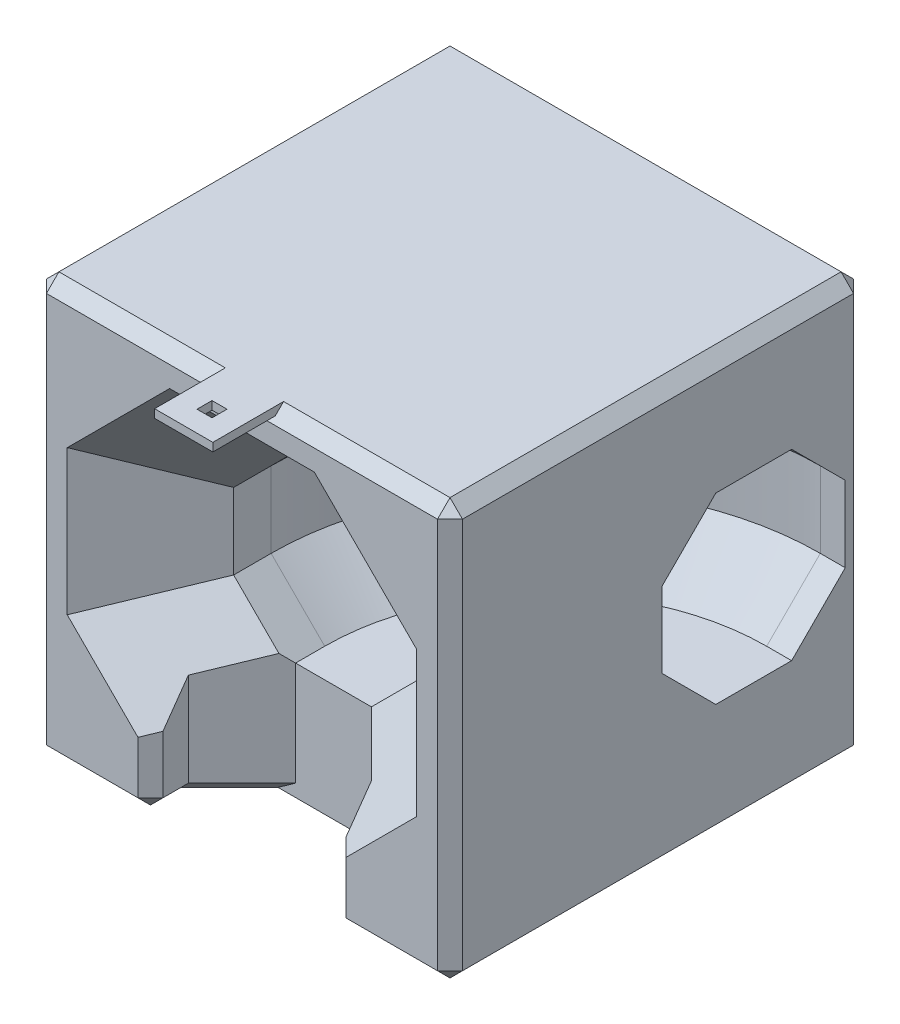
SolidWorks part; units mm, degrees
ref_plane "Front" through (0, 0, 0) normal (0, 0, 1) x (1, 0, 0)
ref_plane "Top" through (0, 0, 0) normal (0, 1, 0) x (1, 0, 0)
ref_plane "Right" through (0, 0, 0) normal (1, 0, 0) x (0, 0, -1)
sketch "Sketch1" plane through (0, 0, 0) normal (0, 0, 1) x (1, 0, 0)
  line L1 (0, 0) -> (50, 0)
  line L2 (0, 0) -> (0, 50)
  line L3 (0, 50) -> (50, 50)
  line L4 (50, 0) -> (50, 50)
  dimension "D1" = 50
extrude "Boss-Extrude1" add sketch "Sketch1" along normal blind 50
ref_plane "Plane1" through (0, 25, 0) normal (0, -1, 0) x (-1, 0, 0)
sketch "Sketch8" plane through (50, 0, 0) normal (1, 0, 0) x (0, 0, -1)
  line L0 (-25, 0) -> (-25, 25) construction
  line L1 (-2.5, 14) -> (-24.5, 14) construction
  line L2 (-2.5, 14) -> (-2.5, 36) construction
  line L3 (-2.5, 36) -> (-24.5, 36) construction
  line L4 (-24.5, 14) -> (-24.5, 36) construction
  line L5 (-2.5, 14) -> (-24.5, 36) construction
  line L6 (-2.5, 36) -> (-24.5, 14) construction
  line L8 (-50, 0) -> (0, 0) construction
  line L10 (-25, 25) -> (-13.5, 25) construction
  line L11 (-2.5, 29.5563) -> (-8.9437, 36)
  line L12 (-8.9437, 36) -> (-18.0563, 36)
  line L13 (-18.0563, 36) -> (-24.5, 29.5563)
  line L14 (-24.5, 29.5563) -> (-24.5, 20.4437)
  line L15 (-24.5, 20.4437) -> (-18.0563, 14)
  line L16 (-18.0563, 14) -> (-8.9437, 14)
  line L17 (-8.9437, 14) -> (-2.5, 20.4437)
  line L18 (-2.5, 20.4437) -> (-2.5, 29.5563)
  line L19 (-13.5, 25) -> (0, 25) construction
  line L20 (0, 0) -> (0, 50) construction
  circle A0 centre (-13.5, 25) radius 11 construction
  point P0 (-13.5, 25)
  dimension "D1" = 22
  dimension "D2" = 2.5
sketch "Sketch9" plane through (0, 25, 0) normal (0, -1, 0) x (-1, 0, 0)
  line L0 (-50, -13.5) -> (-47, -13.5)
  line L1 (-25, -35.5) -> (-25, -50)
  line L2 (-50, -50) -> (0, -50) construction
  arc A0 (-47, -13.5) -> (-25, -35.5) centre (-47, -35.5) cw
  dimension "D2" = 3
sweep "Cut-Sweep5" cut profiles "Sketch8" path "Sketch9"
chamfer "Chamfer1" distance 10 angle 45 8 edges at (36, 25, 50) (32.7782, 32.7782, 50) (25, 36, 50) (17.2218, 32.7782, 50) (14, 25, 50) (17.2218, 17.2218, 50) (25, 14, 50) (32.7782, 17.2218, 50)
sketch "Sketch10" plane through (0, 0, 0) normal (0, -1, 0) x (1, 0, 0)
  line L0 (0, 50) -> (50, 50) construction
  line L1 (29.5563, 39) -> (36, 45.4437)
  line L2 (36, 45.4437) -> (36, 54.5563)
  line L3 (36, 54.5563) -> (29.5563, 61)
  line L4 (29.5563, 61) -> (20.4437, 61)
  line L5 (20.4437, 61) -> (14, 54.5563)
  line L6 (14, 54.5563) -> (14, 45.4437)
  line L7 (14, 45.4437) -> (20.4437, 39)
  line L8 (20.4437, 39) -> (29.5563, 39)
  circle A0 centre (25, 50) radius 11 construction
  dimension "D1" = 22
extrude "Cut-Extrude1" cut sketch "Sketch10" against normal blind 22
chamfer "Chamfer2" distance 1.5 angle 45 19 edges at (25, 50, 50) (0, 25, 50) (25, 50, 0) (0, 50, 25) (0, 25, 0) (50, 50, 25) (50, 25, 0) (50, 25, 50) (36, 3.1508, 50) (32.7782, 0, 42.2218) (36, 0, 47.7218) (43, 0, 50) (50, 0, 25) (25, 0, 0) (0, 0, 25) (7, 0, 50) (14, 3.1508, 50) (14, 0, 47.7218) (17.2218, 0, 42.2218)
sketch "Sketch11" plane through (0, 0, 50) normal (0, 0, 1) x (1, 0, 0)
  line L0 (1.5, 50) -> (48.5, 50) construction
  line L1 (21.5, 50) -> (28.5, 50)
  line L2 (21.5, 50) -> (21.5, 49)
  line L3 (21.5, 49) -> (28.5, 49)
  line L4 (28.5, 50) -> (28.5, 49)
  point P6 (25, 50)
  dimension "D1" = 7
  dimension "D2" = 1
extrude "Boss-Extrude2" add sketch "Sketch11" along normal blind 7 and the other way blind 10
sketch "Sketch12" plane through (0, 49, 0) normal (0, -1, 0) x (1, 0, 0)
  line L0 (25, 54.5) -> (25, 57) construction
  line L1 (24.1, 54.5) -> (25.9, 54.5)
  line L2 (24.1, 54.5) -> (24.1, 52.7)
  line L3 (24.1, 52.7) -> (25.9, 52.7)
  line L4 (25.9, 54.5) -> (25.9, 52.7)
  line L5 (21.5, 57) -> (28.5, 57) construction
  dimension "D1" = 2.5
  dimension "D2" = 1.8
extrude "Cut-Extrude2" cut sketch "Sketch12" against normal blind 7
